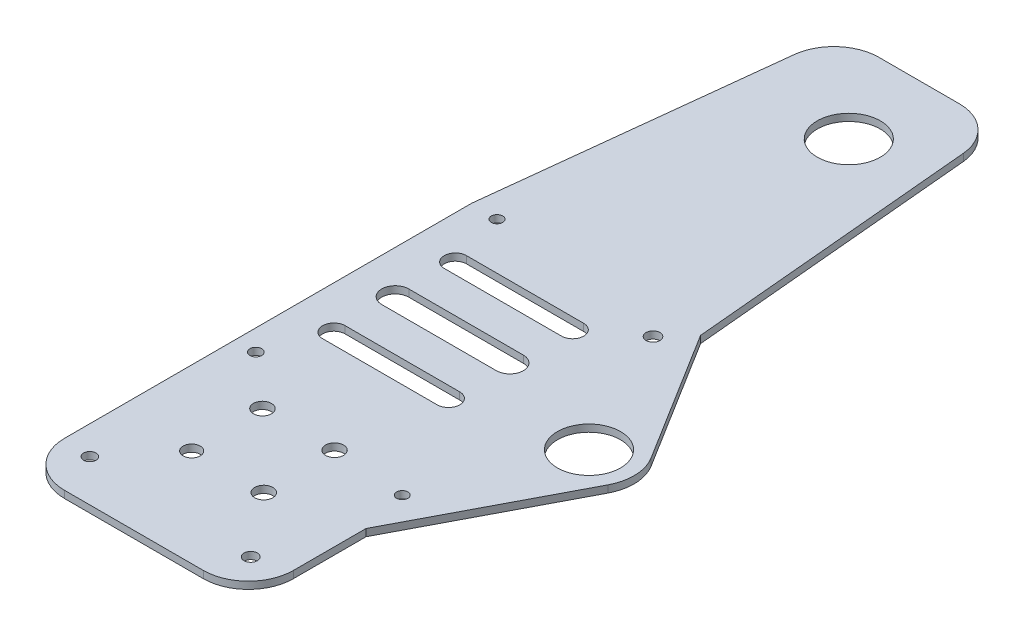
SolidWorks part; units mm, degrees
ref_plane "Front" through (0, 0, 0) normal (0, 0, 1) x (1, 0, 0)
ref_plane "Top" through (0, 0, 0) normal (0, 1, 0) x (1, 0, 0)
ref_plane "Right" through (0, 0, 0) normal (1, 0, 0) x (0, 0, -1)
sketch "Sketch1" plane through (0, 0, 0) normal (0, 1, 0) x (1, 0, 0)
  line L0 (10.4543, 228.6) -> (0, 135.3627)
  line L1 (0, 0) -> (50.8, 0)
  line L2 (0, 0) -> (0, 228.6)
  line L3 (0, 228.6) -> (50.8, 228.6)
  line L4 (50.8, 0) -> (50.8, 228.6)
  line L5 (42.3273, 228.6) -> (50.8, 135.3627)
  line L8 (50.8, 0) -> (24.327, 0)
  line L16 (50.8, 120.6192) -> (50.8, 104.4882)
  line L18 (50.8, 64.8791) -> (50.8, 87.4235)
  line L20 (9.492, 92.7849) -> (34.9257, 92.7849)
  line L21 (9.492, 92.7849) -> (9.492, 97.7849)
  line L22 (9.492, 97.7849) -> (34.9257, 97.7849)
  line L23 (34.9257, 92.7849) -> (34.9257, 97.7849)
  line L25 (9.492, 105.9099) -> (34.9257, 105.9099)
  line L26 (9.492, 105.9099) -> (9.492, 111.9099)
  line L27 (9.492, 111.9099) -> (34.9257, 111.9099)
  line L28 (34.9257, 105.9099) -> (34.9257, 111.9099)
  line L30 (9.492, 119.7849) -> (35.5097, 119.7849)
  line L31 (9.492, 119.7849) -> (9.492, 124.7158)
  line L32 (9.492, 124.7158) -> (35.5097, 124.7158)
  line L33 (35.5097, 119.7849) -> (35.5097, 124.7158)
  circle A12 centre (60.4, 101.001) radius 10
  circle A13 centre (29.5042, 189.5572) radius 7
  circle A22 centre (9.492, 95.2849) radius 2.5
  circle A23 centre (34.9257, 95.2849) radius 2.5
  circle A24 centre (34.9257, 108.9099) radius 3
  circle A25 centre (9.492, 108.9099) radius 3
  circle A26 centre (9.492, 122.2504) radius 2.4654
  circle A27 centre (35.5097, 122.2504) radius 2.4654
  circle A28 centre (16.5455, 56.6667) radius 1.897
  circle A29 centre (32.5429, 56.67) radius 2
  circle A30 centre (32.2518, 72.67) radius 2
  circle A31 centre (16.2545, 72.6667) radius 2
  circle A32 centre (43.4477, 42.8684) radius 1.4834
  circle A33 centre (6.3356, 44.2888) radius 1.3882
  circle A34 centre (4.6595, 82.7932) radius 1.3149
  circle A35 centre (48.401, 71.551) radius 1.2486
  circle A36 centre (45.7477, 129.8635) radius 1.5391
  circle A37 centre (5.8847, 135.1031) radius 1.2556
  dimension "D3" = 20
  dimension "D4" = 103.8842
  dimension "D5" = 16
  dimension "D6" = 14
  dimension "D7" = 116.6901
  dimension "D1" = 50.8
  dimension "D2" = 228.6
  dimension "D8" = 130.8151
  dimension "D9" = 56.6667
  dimension "D10" = 16
extrude "Boss-Extrude1" add sketch "Sketch1" along normal blind 1.5875 contours L1 L4 L3 L0 L2
sketch "Sketch4" plane through (0, 0, -228.6) normal (0, 0, -1) x (-1, 0, 0)
  line L1 (-61.3109, 11.9192) -> (4.9615, 11.9192)
  line L2 (-61.3109, 11.9192) -> (-61.3109, -15.8811)
  line L3 (-61.3109, -15.8811) -> (4.9615, -15.8811)
  line L4 (4.9615, 11.9192) -> (4.9615, -15.8811)
extrude "Cut-Extrude2" cut sketch "Sketch4" against normal blind 20
fillet "Fillet3" radius 10 1 edges at (44.1447, 0.7937, -208.6)
fillet "Fillet4" radius 10 3 edges at (50.8, 0.7937, 0) (0, 0.7937, 0) (8.2118, 0.7937, -208.6)
sketch "Sketch6" plane through (0, 1.5875, 0) normal (0, 1, 0) x (1, 0, 0)
  line L0 (68.8909, 106.2834) -> (50.8, 135.3627)
  line L1 (50.8, 135.3627) -> (50.8, 103.801)
  line L2 (69.2582, 96.3607) -> (50.8, 61.1242)
  line L3 (50.8, 10) -> (50.8, 98.201) construction
  line L4 (50.8, 61.1242) -> (50.8, 96.3607)
  line L5 (50.8, 96.3607) -> (50.8, 98.201)
  circle A0 centre (60.4, 101.001) radius 10
extrude "Boss-Extrude3" add sketch "Sketch6" against normal blind 1.5875
sketch "Sketch7" plane through (0, 1.5875, 0) normal (0, 1, 0) x (1, 0, 0)
  circle A0 centre (60.4, 101.001) radius 7
  dimension "D1" = 14
extrude "Cut-Extrude3" cut sketch "Sketch7" against normal blind 1.5875
sketch "Sketch8" plane through (0, 0, 0) normal (0, 0, 1) x (1, 0, 0)
  line L1 (-21.5979, 31.8127) -> (78.5082, 31.8127)
  line L2 (-21.5979, 31.8127) -> (-21.5979, -28.4046)
  line L3 (-21.5979, -28.4046) -> (78.5082, -28.4046)
  line L4 (78.5082, 31.8127) -> (78.5082, -28.4046)
extrude "Cut-Extrude4" cut sketch "Sketch8" against normal blind 35
fillet "Fillet5" radius 10 2 edges at (0, 0.7937, -35) (50.8, 0.7937, -35)
equation "\"7i\"=101.6"
